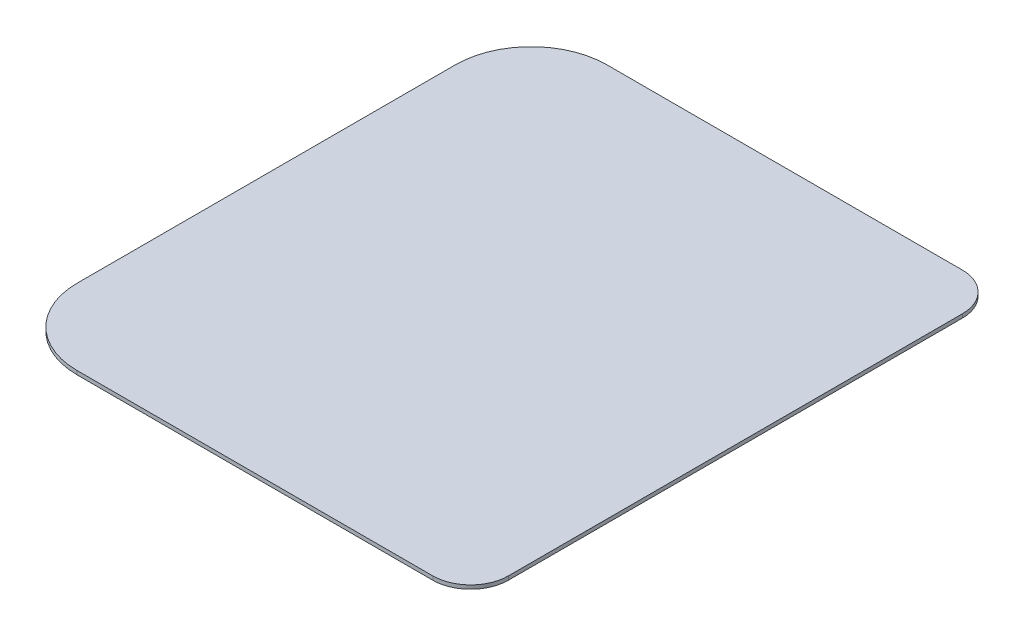
SolidWorks part; units mm, degrees
material "Acrylic (Medium-high impact)"
ref_plane "Front Plane" through (0, 0, 0) normal (0, 0, 1) x (1, 0, 0)
ref_plane "Top Plane" through (0, 0, 0) normal (0, 1, 0) x (1, 0, 0)
ref_plane "Right Plane" through (0, 0, 0) normal (1, 0, 0) x (0, 0, -1)
sketch "Sketch1" plane through (0, 0, 0) normal (0, 1, 0) x (1, 0, 0)
  line L1 (-210, -350) -> (260, -350)
  line L2 (-310, -250) -> (-310, 250)
  line L3 (-210, 350) -> (260, 350)
  line L4 (310, -300) -> (310, 300)
  line L5 (-310, -350) -> (310, 350) construction
  line L6 (-310, 350) -> (310, -350) construction
  arc A0 (-210, -350) -> (-310, -250) centre (-210, -250) cw
  arc A1 (-310, 250) -> (-210, 350) centre (-210, 250) cw
  arc A2 (310, -300) -> (260, -350) centre (260, -300) cw
  arc A3 (310, 300) -> (260, 350) centre (260, 300) ccw
  point P0 (0, 0)
  dimension "D3" = 100
  dimension "D4" = 50
  dimension "D1" = 700
  dimension "D2" = 620
extrude "Boss-Extrude1" add sketch "Sketch1" along normal blind 5
